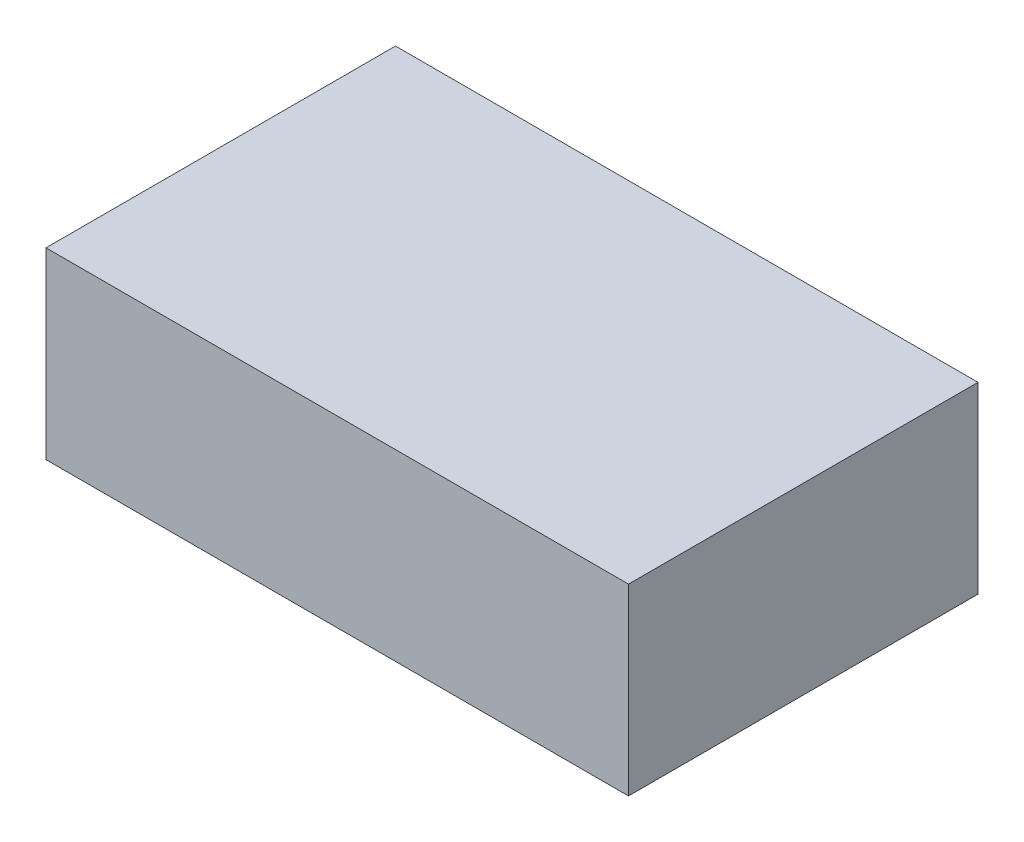
SolidWorks part; units mm, degrees
ref_plane "Front" through (0, 0, 0) normal (0, 0, 1) x (1, 0, 0)
ref_plane "Top" through (0, 0, 0) normal (0, 1, 0) x (1, 0, 0)
ref_plane "Right" through (0, 0, 0) normal (1, 0, 0) x (0, 0, -1)
sketch "Sketch1" plane through (0, 0, 0) normal (0, 1, 0) x (1, 0, 0)
  line L1 (0, 0) -> (38.1, 0)
  line L2 (0, 0) -> (0, 22.86)
  line L3 (0, 22.86) -> (38.1, 22.86)
  line L4 (38.1, 0) -> (38.1, 22.86)
  dimension "D1" = 22.86
  dimension "D2" = 38.1
extrude "Boss-Extrude1" add sketch "Sketch1" along normal blind 12
